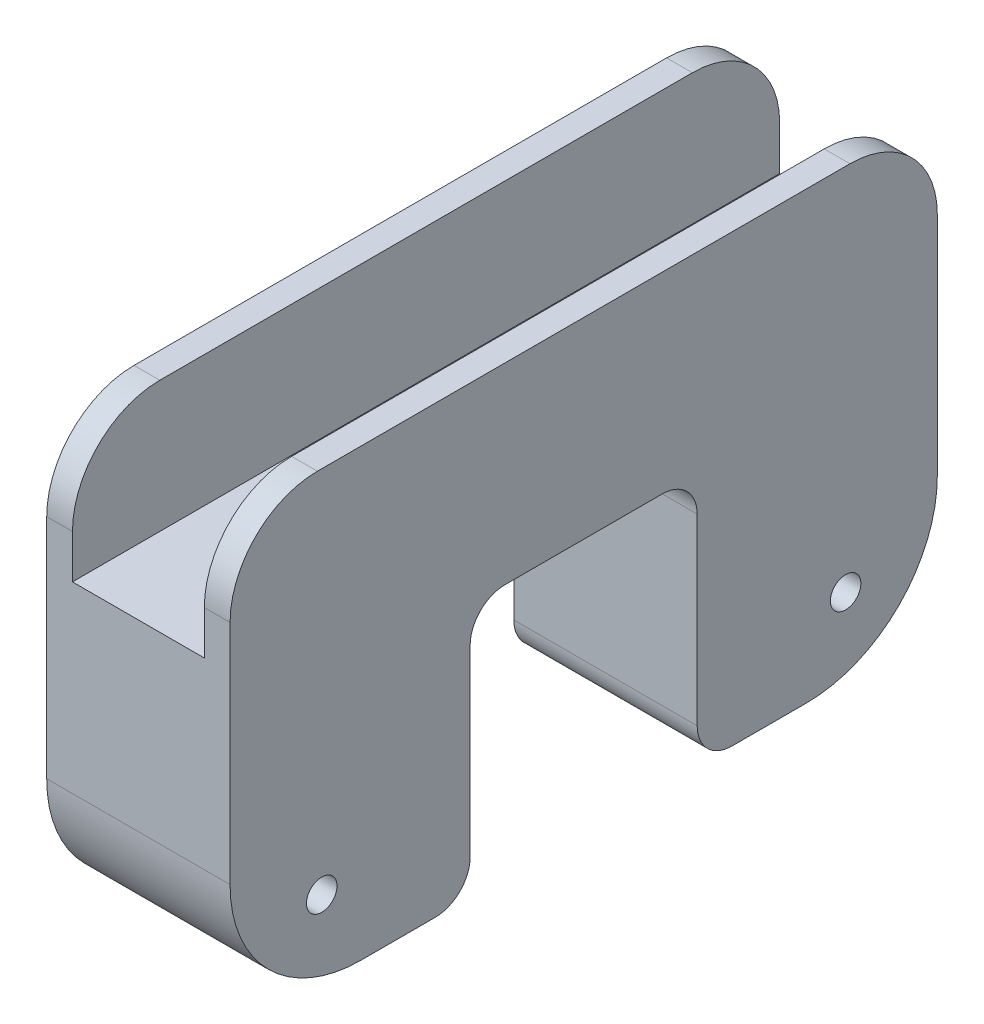
SolidWorks part; units mm, degrees
ref_plane "前视基准面" through (0, 0, 0) normal (0, 0, 1) x (1, 0, 0)
ref_plane "上视基准面" through (0, 0, 0) normal (0, 1, 0) x (1, 0, 0)
ref_plane "右视基准面" through (0, 0, 0) normal (1, 0, 0) x (0, 0, -1)
other "Configuration Table"
sketch "草图1" plane through (0, 0, 0) normal (0, 0, 1) x (1, 0, 0)
  line L0 (10.5, 0) -> (10.5, -51) construction
  line L1 (0, 0) -> (21, 0)
  line L2 (0, 0) -> (0, -51)
  line L3 (0, -51) -> (21, -51)
  line L4 (21, 0) -> (21, -51)
  line L6 (2.95, 0) -> (18.05, 0)
  line L7 (2.95, 0) -> (2.95, -15)
  line L8 (2.95, -15) -> (18.05, -15)
  line L9 (18.05, 0) -> (18.05, -15)
  dimension "D1" = 21
  dimension "D2" = 51
  dimension "D3" = 15.1
  dimension "D4" = 15
extrude "凸台-拉伸1" add sketch "草图1" along normal blind 81 contours L8 L0 L3 L4 L1 L9 | L0 L8 L7 L1 L2 L3
sketch "草图2" plane through (0, -51, 0) normal (0, -1, 0) x (1, 0, 0)
  line L0 (10.5, 81) -> (10.5, 0) construction
  line L1 (0, 81) -> (21, 81) construction
  line L2 (0, 0) -> (21, 0) construction
  circle A1 centre (10.5, 20.5) radius 2.25
  circle A2 centre (10.5, 60.5) radius 2.25
  dimension "D1" = 40
  dimension "D3" = 4.5
  dimension "D2" = 20.5
extrude "切除-拉伸1" cut sketch "草图2" against normal blind 82
sketch "草图3" plane through (21, 0, 0) normal (1, 0, 0) x (0, 0, -1)
  line L0 (-81, -42.25) -> (0, -42.25) construction
  line L1 (-81, 0) -> (-81, -51) construction
  line L2 (0, 0) -> (0, -51) construction
  line L3 (-81, -51) -> (0, -51) construction
  line L4 (-40.5, 0) -> (-40.5, -51) construction
  line L5 (-81, 0) -> (0, 0) construction
  circle A0 centre (-70.5, -42.25) radius 1.75
  circle A1 centre (-10.5, -42.25) radius 1.75
  dimension "D2" = 60
  dimension "D3" = 3.5
  dimension "D1" = 8.75
extrude "切除-拉伸2" cut sketch "草图3" against normal blind 82
sketch "草图4" plane through (0, 0, 0) normal (-1, 0, 0) x (0, 0, 1)
  line L4 (0, 0) -> (0, -51)
  line L5 (0, -51) -> (81, -51)
  line L6 (81, -51) -> (81, 0)
  line L7 (81, 0) -> (0, 0)
  line L8 (0, 0) -> (0, -51)
  line L9 (0, -51) -> (81, -51)
  line L10 (81, -51) -> (81, 0)
  line L11 (81, 0) -> (0, 0)
  circle A0 centre (10.5, -42.25) radius 1.75 construction
  circle A1 centre (10.5, -42.25) radius 1.75
  circle A2 centre (70.5, -42.25) radius 1.75 construction
  circle A3 centre (70.5, -42.25) radius 1.75
  dimension "D1" = 0
fillet "圆角1" radius 10 4 edges at (1.475, 0, 0) (19.525, 0, 0) (19.525, 0, 81) (1.475, 0, 81)
fillet "圆角3" radius 15 2 edges at (10.5, -51, 0) (10.5, -51, 81)
sketch "草图5" plane through (21, 0, 0) normal (1, 0, 0) x (0, 0, -1)
  line L0 (-40.5, 0) -> (-40.5, -51) construction
  line L1 (-66, -26) -> (-15, -26)
  line L2 (-66, -26) -> (-66, -51)
  line L3 (-66, -51) -> (-15, -51)
  line L4 (-66, -51) -> (-15, -51)
  line L5 (0, -36) -> (0, -10)
  line L6 (-10, 0) -> (-71, 0)
  line L7 (-81, -10) -> (-81, -36)
  line L8 (-66, -51) -> (-15, -51)
  line L9 (0, -36) -> (0, -10)
  line L10 (-10, 0) -> (-71, 0)
  line L11 (-81, -10) -> (-81, -36)
  line L12 (-15, -26) -> (-15, -51)
  arc A0 (-81, -36) -> (-66, -51) centre (-66, -36) ccw construction
  arc A4 (-15, -51) -> (0, -36) centre (-15, -36) ccw
  arc A5 (0, -10) -> (-10, 0) centre (-10, -10) ccw
  arc A6 (-71, 0) -> (-81, -10) centre (-71, -10) ccw
  arc A7 (-81, -36) -> (-66, -51) centre (-66, -36) ccw
  arc A8 (-15, -51) -> (0, -36) centre (-15, -36) ccw
  arc A9 (0, -10) -> (-10, 0) centre (-10, -10) ccw
  arc A10 (-71, 0) -> (-81, -10) centre (-71, -10) ccw
  arc A11 (-81, -36) -> (-66, -51) centre (-66, -36) ccw
  dimension "D2" = 25
  dimension "D1" = 0
sketch "草图6" plane through (21, 0, 0) normal (1, 0, 0) x (0, 0, -1)
  line L0 (-40.5, 0) -> (-40.5, -51) construction
  line L1 (-53.5, -22) -> (-27.5, -22)
  line L2 (-53.5, -22) -> (-53.5, -51)
  line L3 (-53.5, -51) -> (-27.5, -51)
  line L4 (-66, -51) -> (-15, -51)
  line L5 (0, -36) -> (0, -10)
  line L6 (-10, 0) -> (-71, 0)
  line L7 (-81, -10) -> (-81, -36)
  line L8 (-66, -51) -> (-15, -51)
  line L9 (0, -36) -> (0, -10)
  line L10 (-10, 0) -> (-71, 0)
  line L11 (-81, -10) -> (-81, -36)
  line L12 (-27.5, -22) -> (-27.5, -51)
  arc A4 (-15, -51) -> (0, -36) centre (-15, -36) ccw
  arc A5 (0, -10) -> (-10, 0) centre (-10, -10) ccw
  arc A6 (-71, 0) -> (-81, -10) centre (-71, -10) ccw
  arc A7 (-81, -36) -> (-66, -51) centre (-66, -36) ccw
  arc A8 (-15, -51) -> (0, -36) centre (-15, -36) ccw
  arc A9 (0, -10) -> (-10, 0) centre (-10, -10) ccw
  arc A10 (-71, 0) -> (-81, -10) centre (-71, -10) ccw
  arc A11 (-81, -36) -> (-66, -51) centre (-66, -36) ccw
  line M16 (-66, -51) -> (-15, -51)
  dimension "D2" = 26
  dimension "D3" = 29
  dimension "D1" = 0
extrude "切除-拉伸3" cut sketch "草图6" against normal blind 55 contours L1 L0 L8 L12 | L0 L1 L2 M16
fillet "圆角4" radius 4 4 edges at (10.5, -22, 53.5) (10.5, -22, 27.5) (10.5, -51, 27.5) (10.5, -51, 53.5)
